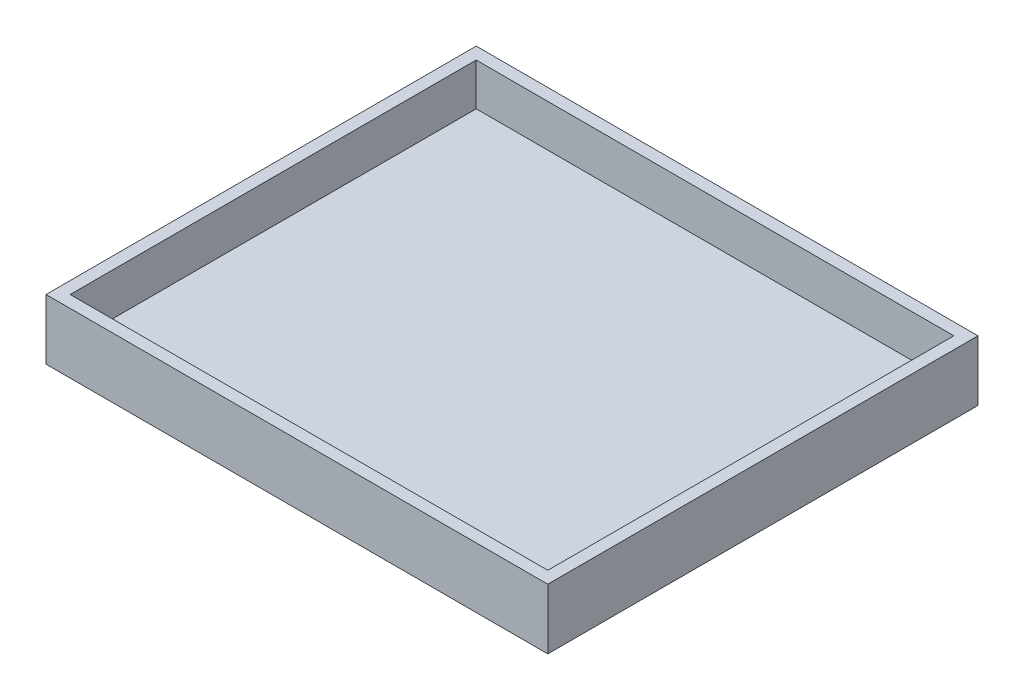
SolidWorks part; units mm, degrees
ref_plane "Front Plane" through (0, 0, 0) normal (0, 0, 1) x (1, 0, 0)
ref_plane "Top Plane" through (0, 0, 0) normal (0, 1, 0) x (1, 0, 0)
ref_plane "Right Plane" through (0, 0, 0) normal (1, 0, 0) x (0, 0, -1)
sketch "Sketch1" plane through (0, 0, 0) normal (0, 1, 0) x (1, 0, 0)
  line L1 (-38.07, 32.64) -> (38.07, 32.64) construction
  line L2 (-38.07, 32.64) -> (-38.07, -32.64) construction
  line L3 (-38.07, -32.64) -> (38.07, -32.64) construction
  line L4 (38.07, 32.64) -> (38.07, -32.64) construction
  line L5 (-38.07, 32.64) -> (38.07, -32.64) construction
  line L6 (-38.07, -32.64) -> (38.07, 32.64) construction
  line L7 (-39.57, 33.9261) -> (39.57, 33.9261) construction
  line L8 (-39.57, 33.9261) -> (-39.57, -33.9261) construction
  line L9 (-39.57, -33.9261) -> (39.57, -33.9261) construction
  line L10 (39.57, 33.9261) -> (39.57, -33.9261) construction
  line L11 (-39.57, 33.9261) -> (39.57, -33.9261) construction
  line L12 (-39.57, -33.9261) -> (39.57, 33.9261) construction
  line L13 (-35.07, 30.0679) -> (35.07, 30.0679) construction
  line L14 (-35.07, 30.0679) -> (-35.07, -30.0679) construction
  line L15 (-35.07, -30.0679) -> (35.07, -30.0679) construction
  line L16 (35.07, 30.0679) -> (35.07, -30.0679) construction
  line L17 (-35.07, 30.0679) -> (35.07, -30.0679) construction
  line L18 (-35.07, -30.0679) -> (35.07, 30.0679) construction
  line L19 (-41.57, 35.6408) -> (41.57, 35.6408)
  line L20 (-41.57, 35.6408) -> (-41.57, -35.6408)
  line L21 (-41.57, -35.6408) -> (41.57, -35.6408)
  line L22 (41.57, 35.6408) -> (41.57, -35.6408)
  line L23 (-41.57, 35.6408) -> (41.57, -35.6408) construction
  line L24 (-41.57, -35.6408) -> (41.57, 35.6408) construction
  point P0 (0, 0)
  point P6 (0, 0)
  point P11 (0, 0)
  point P16 (0, 0)
  dimension "D1" = 65.28
  dimension "D2" = 76.14
  dimension "D3" = 1.5
  dimension "D4" = 70.14
  dimension "D5" = 60.1358
  dimension "D6" = 2
extrude "Boss-Extrude1" add sketch "Sketch1" along normal blind 10
sketch "Sketch2" plane through (0, 10, 0) normal (0, 1, 0) x (1, 0, 0)
  line L0 (-41.57, 35.6408) -> (-41.57, -35.6408) construction
  line L1 (-39.57, 33.6408) -> (39.57, 33.6408)
  line L2 (-39.57, 33.6408) -> (-39.57, -33.6408)
  line L3 (-39.57, -33.6408) -> (39.57, -33.6408)
  line L4 (39.57, 33.6408) -> (39.57, -33.6408)
  line L5 (-39.57, 33.6408) -> (39.57, -33.6408) construction
  line L6 (-39.57, -33.6408) -> (39.57, 33.6408) construction
  line L7 (41.57, 35.6408) -> (-41.57, 35.6408) construction
  point P0 (0, 0)
  dimension "D1" = 2
  dimension "D2" = 2
extrude "Cut-Extrude1" cut sketch "Sketch2" against normal blind 7
